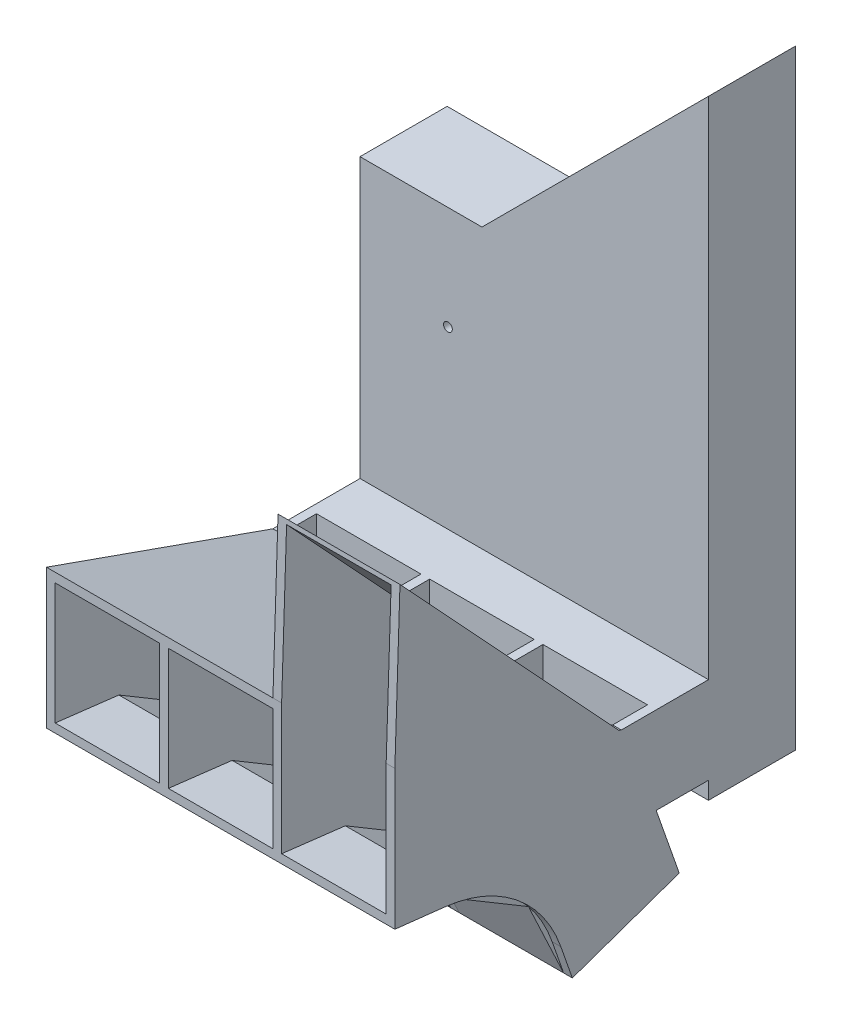
SolidWorks part; units mm, degrees
ref_plane "Přední rovina" through (0, 0, 0) normal (0, 0, 1) x (1, 0, 0)
ref_plane "Horní rovina" through (0, 0, 0) normal (0, 1, 0) x (1, 0, 0)
ref_plane "Pravá rovina" through (0, 0, 0) normal (1, 0, 0) x (0, 0, -1)
sketch "Skica1" plane through (0, 0, 0) normal (0, 0, 1) x (1, 0, 0)
  line L0 (0, 0) -> (200, 0)
  line L1 (200, 0) -> (200, 350)
  line L2 (200, 350) -> (70, 220)
  line L3 (70, 220) -> (0, 220)
  line L4 (0, 220) -> (0, 0)
  dimension "D1" = 350
  dimension "D2" = 200
  dimension "D3" = 70
  dimension "D4" = 220
extrude "Přidat vysunutím1" add sketch "Skica1" along normal blind 50
sketch "Skica7" plane through (0, 0, 50) normal (0, 0, 1) x (1, 0, 0)
  line L0 (0, 220) -> (0, 0) construction
  line L1 (0, 10) -> (200, 10)
  line L2 (0, 10) -> (0, 60)
  line L3 (0, 60) -> (200, 60)
  line L4 (200, 10) -> (200, 60)
  line L5 (200, 0) -> (200, 350) construction
  line L6 (0, 0) -> (200, 0) construction
  dimension "D1" = 50
  dimension "D2" = 10
extrude "Přidat vysunutím5" add sketch "Skica7" along normal blind 30
sketch "Skica9" plane through (0, 0, 0) normal (-1, 0, 0) x (0, 0, 1)
  line L0 (80, 10) -> (66.7748, -27.7504)
  line L2 (66.7748, -27.7504) -> (128.1192, -49.2414)
  line L3 (128.1192, -49.2414) -> (134.7318, -30.3662)
  line L4 (201.2747, 22.6803) -> (230, 25.9171)
  line L5 (230, 25.9171) -> (230, 105.9171)
  line L6 (230, 105.9171) -> (100, 60)
  line L7 (100, 60) -> (80, 60)
  line L8 (80, 60) -> (80, 10)
  arc A0 (134.7318, -30.3662) -> (201.2747, 22.6803) centre (210.2326, -56.8166) cw
  point P12 (293.0849, 101.0177)
  point P13 (248.1985, 97.3869)
  dimension "D1" = 80
  dimension "D2" = 65
  dimension "D3" = 80
  dimension "D4" = 20
  dimension "D5" = 130
  dimension "D6" = 40
  dimension "D7" = 20
  dimension "D8" = 160.693
extrude "Přidat vysunutím6" add sketch "Skica9" against normal blind 5
pattern_linear "LinPole1" count 4 spacing 65 along (1, 0, 0) of "Přidat vysunutím6"
sketch "Skica12" plane through (5, 0, 0) normal (1, 0, 0) x (0, 0, -1)
  line L0 (-230, 105.9171) -> (-230, 100.6144)
  line L1 (-230, 25.9171) -> (-230, 105.9171) construction
  line L2 (-230, 100.6144) -> (-105.2203, 56.5411)
  line L3 (-105.2203, 56.5411) -> (-71.4968, -29.4047)
  line L4 (-66.7748, -27.7504) -> (-128.1192, -49.2414) construction
  line L5 (-71.4968, -29.4047) -> (-66.7748, -27.7504)
  line L6 (-66.7748, -27.7504) -> (-101.4004, 60.4946)
  line L7 (-230, 105.9171) -> (-100, 60) construction
  line L8 (-101.4004, 60.4946) -> (-230, 105.9171)
  line L9 (-230, 25.9171) -> (-230, 30.9529)
  line L10 (-230, 30.9529) -> (-193.4216, 26.5716)
  line L11 (-193.4216, 26.5716) -> (-144.4818, -2.5962)
  line L12 (-144.4818, -2.5962) -> (-123.3759, -47.5797)
  line L13 (-123.3759, -47.5797) -> (-128.1192, -49.2414)
  line L14 (-128.1192, -49.2414) -> (-148.3576, -6.1069)
  line L15 (-148.3576, -6.1069) -> (-195.0698, 21.7333)
  line L16 (-195.0698, 21.7333) -> (-230, 25.9171)
  line L17 (-201.2747, 22.6803) -> (-230, 25.9171) construction
  arc A0 (-134.7318, -30.3662) -> (-201.2747, 22.6803) centre (-210.2326, -56.8166) ccw construction
  point P17 (-182.076, 33.0646)
  point P28 (0, 0)
  point P29 (-230, 42.7503)
  point P30 (0, 0)
  point P31 (-230, 52.2547)
  point P32 (-230, 47.5565)
  point P33 (-230, 43.3119)
  dimension "D1" = 5
  dimension "D2" = 5
  dimension "D3" = 94.7952
  dimension "D4" = 5
  dimension "D5" = 5
  dimension "D6" = 5
  dimension "D7" = 35.1798
  dimension "D8" = 54.3793
extrude "Přidat vysunutím10" add sketch "Skica12" along normal blind 60
pattern_linear "LinPole3" count 3 spacing 65 along (1, 0, 0) of "Přidat vysunutím10"
sketch "Skica16" plane through (0, 0, 230) normal (0, 0, 1) x (1, 0, 0)
  line L0 (165, 30.9529) -> (165, 287.5295) construction
  line L1 (195, 30.9529) -> (135, 30.9529) construction
  line L2 (100, 30.9529) -> (100, 240.3599) construction
  line L3 (130, 30.9529) -> (70, 30.9529) construction
  line L4 (35, 30.9529) -> (35, 225.5826) construction
  line L5 (65, 30.9529) -> (5, 30.9529) construction
  line L7 (133.4722, 193.1032) -> (194.1802, 193.1032)
  line L8 (133.4722, 193.1032) -> (133.4722, 128.1032)
  line L9 (133.4722, 128.1032) -> (194.1802, 128.1032)
  line L10 (194.1802, 193.1032) -> (194.1802, 128.1032)
  line L11 (133.4722, 193.1032) -> (194.1802, 128.1032) construction
  line L12 (133.4722, 128.1032) -> (194.1802, 193.1032) construction
  circle A0 centre (50.4595, 160.6032) radius 113.3667
  point P14 (163.8262, 160.6032)
  dimension "D1" = 65
sketch "Skica17" plane through (0, 21.9418, -7.75) normal (0, 0.9429, -0.333) x (1, 0, 0)
  line L0 (200, -252.1447) -> (200, -114.2738) construction
  line L1 (195, -252.1447) -> (135, -252.1447)
  line L2 (195, -252.1447) -> (195, -119.8147)
  line L3 (195, -119.8147) -> (135, -119.8147)
  line L4 (135, -252.1447) -> (135, -119.8147)
  line L6 (200, -252.1447) -> (0, -252.1447) construction
  dimension "D1" = 60
  dimension "D2" = 5
  dimension "D3" = 132.33
  dimension "D4" = 0
extrude "Odebrat vysunutím3" cut sketch "Skica17" against normal blind 10
sketch "Skica18" plane through (135, 0, 0) normal (1, 0, 0) x (0, 0, -1)
  line L0 (-101.4004, 60.4946) -> (-227.0714, 195.8695)
  line L1 (-227.0714, 195.8695) -> (-230, 105.9171)
  line L2 (-230, 105.9171) -> (-101.4004, 60.4946)
  dimension "D1" = 90
  dimension "D2" = 184.7148
extrude "Přidat vysunutím12" add sketch "Skica18" against normal blind 5
pattern_linear "LinPole4" count 2 spacing 65 along (1, 0, 0) of "Přidat vysunutím12"
sketch "Skica19" plane through (135, 0, 0) normal (1, 0, 0) x (0, 0, -1)
  line L0 (-227.0714, 195.8695) -> (-101.4004, 60.4946)
  line L1 (-101.4004, 60.4946) -> (-105.2246, 61.8454)
  line L2 (-105.2246, 61.8454) -> (-227.1585, 193.1946)
  line L3 (-227.0714, 195.8695) -> (-230, 105.9171) construction
  line L4 (-227.1585, 193.1946) -> (-227.0714, 195.8695)
extrude "Přidat vysunutím13" add sketch "Skica19" along normal blind 60
sketch "Skica20" plane through (0, 0, 50) normal (0, 0, 1) x (1, 0, 0)
  circle A0 centre (50.4595, 160.6032) radius 2.5
  dimension "D1" = 5
extrude "Odebrat vysunutím4" cut sketch "Skica20" against normal blind 10
